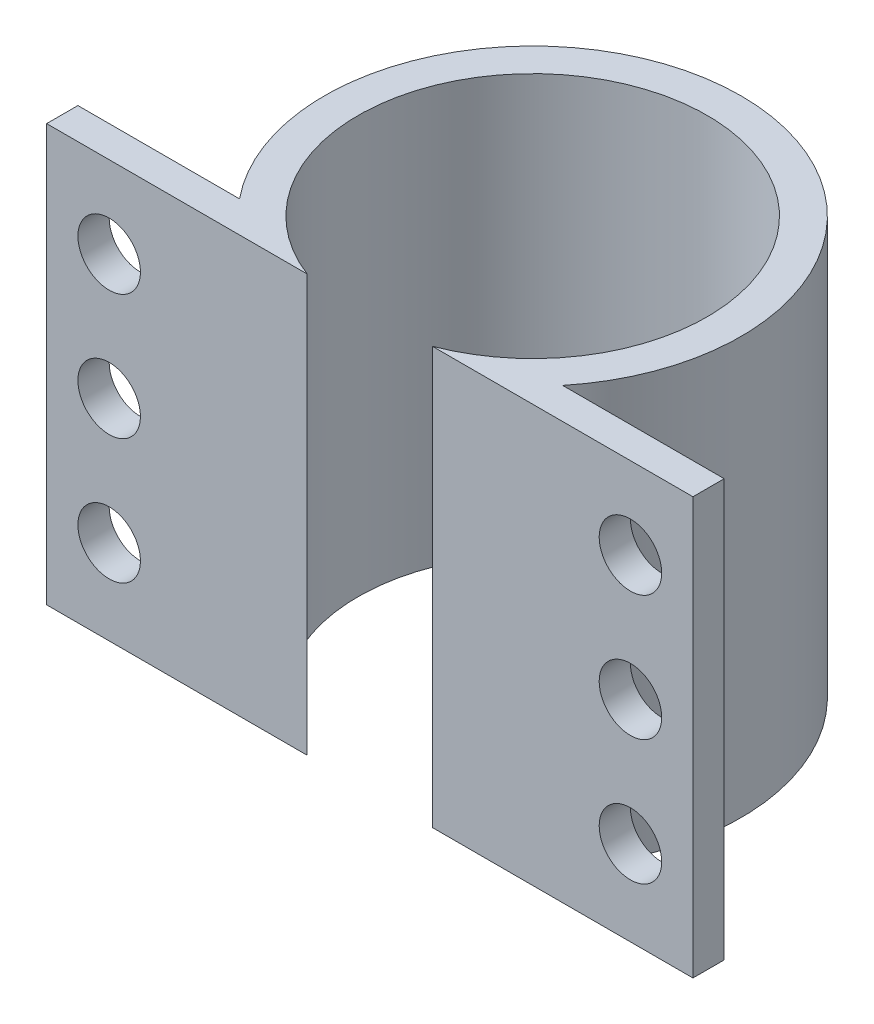
SolidWorks part; units mm, degrees
material "PET"
ref_plane "Alzado" through (0, 0, 0) normal (0, 0, 1) x (1, 0, 0)
ref_plane "Planta" through (0, 0, 0) normal (0, 1, 0) x (1, 0, 0)
ref_plane "Vista lateral" through (0, 0, 0) normal (1, 0, 0) x (0, 0, -1)
sketch "Croquis1" plane through (0, 0, 0) normal (0, 1, 0) x (1, 0, 0)
  line L33 (6.0134, -15.6333) -> (31.0134, -15.6333)
  line L35 (-31.0134, -12.6333) -> (-31.0134, -15.6333)
  line L36 (-31.0134, -15.6333) -> (-6.0134, -15.6333)
  line L37 (31.0134, -15.6333) -> (31.0134, -12.6333)
  line L39 (-31.3515, -12.6333) -> (-31.3515, -12.5667) construction
  line L40 (-31.0134, -12.6333) -> (-15.5048, -12.6333)
  line L41 (15.5048, -12.6333) -> (31.0134, -12.6333)
  line L42 (0, 0) -> (0, -10.0378) construction
  arc A2 (6.0134, -15.6333) -> (-6.0134, -15.6333) centre (0, 0) ccw
  arc A5 (15.5048, -12.6333) -> (-15.5048, -12.6333) centre (0, 0) ccw
  point P4 (0, 0)
  dimension "D1" = 16.75
  dimension "D3" = 33.5
  dimension "D4" = 3
  dimension "D7" = 20
  dimension "D5" = 25
  dimension "D6" = 3
  dimension "27" = 25
extrude "Saliente-Extruir1" add sketch "Croquis1" along normal blind 40
sketch "Croquis2" plane through (0, 0, 12.6333) normal (0, 0, -1) x (-1, 0, 0)
  line L0 (0, -8.2755) -> (0, 67.2225) construction
  line L1 (31.0134, 40) -> (31.0134, 0) construction
  line L2 (-31.0134, 40) -> (-31.0134, 0) construction
  circle A0 centre (25.0134, 8.1544) radius 3
  circle A1 centre (25.0134, 20.1544) radius 3
  circle A2 centre (25.0134, 32.1544) radius 3
  circle A3 centre (-25.0134, 32.1544) radius 3
  circle A4 centre (-25.0134, 8.1544) radius 3
  circle A5 centre (-25.0134, 20.1544) radius 3
  dimension "D1" = 6
  dimension "D3" = 6
  dimension "D4" = 6
  dimension "D5" = 12
  dimension "D6" = 12
  dimension "D2" = 6
extrude "Cortar-Extruir1" cut sketch "Croquis2" against normal blind 10
